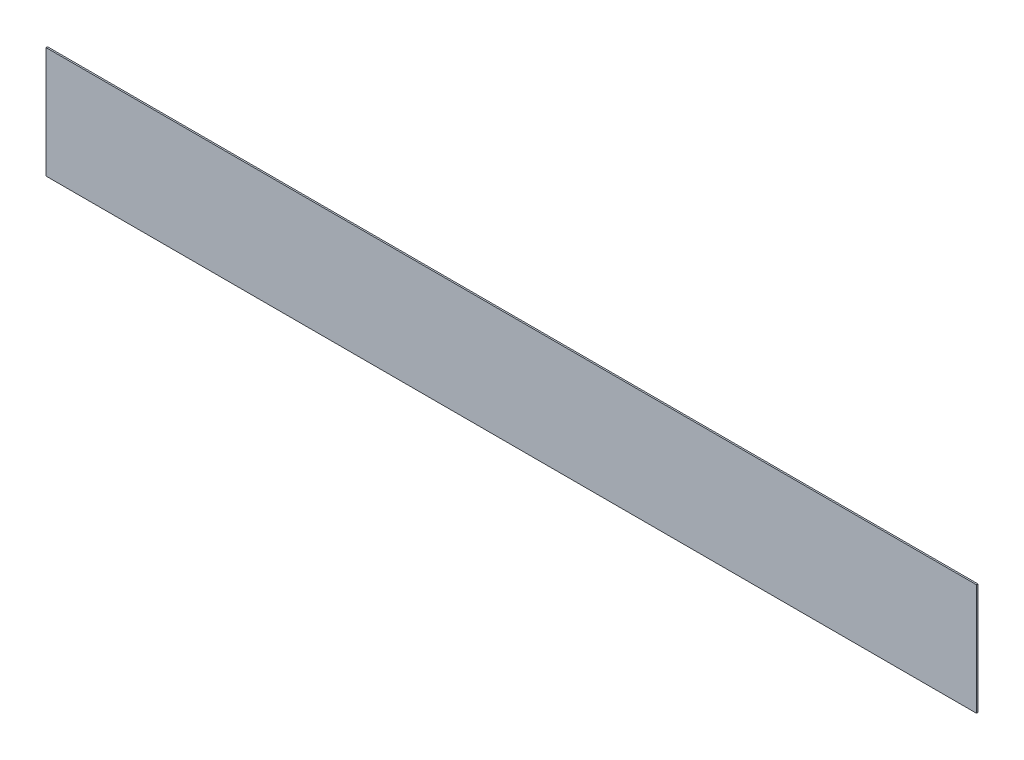
SolidWorks part; units mm, degrees
material "ABS"
ref_plane "Front Plane" through (0, 0, 0) normal (0, 0, 1) x (1, 0, 0)
ref_plane "Top Plane" through (0, 0, 0) normal (0, 1, 0) x (1, 0, 0)
ref_plane "Right Plane" through (0, 0, 0) normal (1, 0, 0) x (0, 0, -1)
sketch "Sketch1" plane through (0, 0, 0) normal (0, 0, 1) x (1, 0, 0)
  line L0 (-1254, 0) -> (0, 0) construction
  line L1 (-1254, 150) -> (1254, 150)
  line L2 (-1254, 150) -> (-1254, -150)
  line L3 (-1254, -150) -> (1254, -150)
  line L4 (1254, 150) -> (1254, -150)
  line L5 (0, 0) -> (1254, 0) construction
  dimension "D1" = 300
  dimension "D2" = 2508
extrude "Boss-Extrude1" add sketch "Sketch1" along normal blind 4
